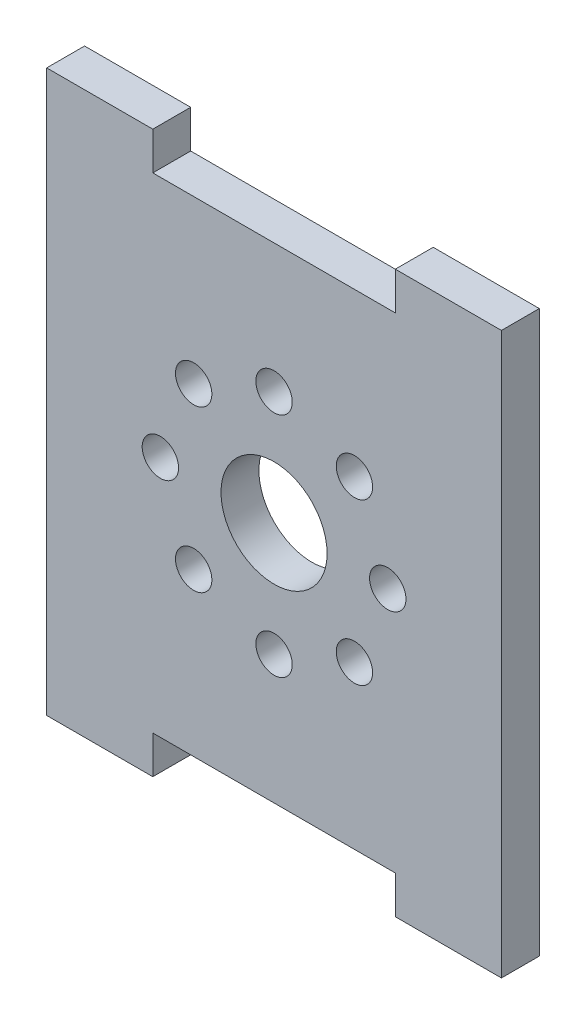
SolidWorks part; units mm, degrees
ref_plane "Plan de face" through (0, 0, 0) normal (0, 0, 1) x (1, 0, 0)
ref_plane "Plan de dessus" through (0, 0, 0) normal (0, 1, 0) x (1, 0, 0)
ref_plane "Plan de droite" through (0, 0, 0) normal (1, 0, 0) x (0, 0, -1)
sketch "Esquisse1" plane through (0, 0, 0) normal (0, 0, 1) x (1, 0, 0)
  line L1 (15, -18.5) -> (-15, -18.5)
  line L2 (15, -18.5) -> (15, 18.5)
  line L3 (15, 18.5) -> (-15, 18.5)
  line L4 (-15, -18.5) -> (-15, 18.5)
  line L5 (15, -18.5) -> (-15, 18.5) construction
  line L6 (15, 18.5) -> (-15, -18.5) construction
  line L7 (8, 16) -> (-8, 16)
  line L8 (8, 16) -> (8, 18.5)
  line L9 (8, 18.5) -> (-8, 18.5)
  line L10 (-8, 16) -> (-8, 18.5)
  line L11 (8, 16) -> (-8, 18.5) construction
  line L12 (8, 18.5) -> (-8, 16) construction
  line L13 (-8, -16) -> (8, -16)
  line L14 (-8, -16) -> (-8, -18.5)
  line L15 (-8, -18.5) -> (8, -18.5)
  line L16 (8, -16) -> (8, -18.5)
  line L17 (-8, -16) -> (8, -18.5) construction
  line L18 (-8, -18.5) -> (8, -16) construction
  circle A0 centre (0, 0) radius 3.5
  point P0 (0, 0)
  point P6 (0, 17.25)
  point P11 (0, -17.25)
  dimension "D7" = 7
  dimension "D1" = 30
  dimension "D2" = 32
  dimension "D3" = 2.5
  dimension "D4" = 2.5
  dimension "D5" = 7
  dimension "D6" = 7
extrude "Boss.-Extru.1" add sketch "Esquisse1" along normal blind 2.5 contours L13 L16 L1 L2 L3 L8 L7 L10 L4 L14 A0
hole_wizard "Dégagement M21" positions "Esquisse5" profile "Esquisse3" hole size "M2" standard "Iso"
sketch "Esquisse5" plane through (0, 0, 2.5) normal (0, 0, 1) x (1, 0, 0)
  point P0 (0, 7.5)
  dimension "D1" = 7.5
sketch "Esquisse3" plane through (0, 7.5, 2.5) normal (1, 0, 0) x (0, -1, 0)
  line L0 (0, 0) -> (0, 3.221)
  line L1 (0, 3.221) -> (1.2, 2.5)
  line L2 (1.2, 2.5) -> (1.2, 0)
  line L5 (1.2, 0) -> (0, 0)
  line L10 (0, 3.221) -> (-1.2, 2.5) construction
  line L11 (0, -6.35) -> (0, 107.95) construction
  dimension "Diamètre du perçage" = 2.4
  dimension "Profondeur du perçage" = 2.5
  dimension "Angle de pointe" = 118
pattern_circular "Répétition circulaire1" count 8 over 360 about axis through (0, 0, 0) along (0, 0, 1) of "Dégagement M21"
